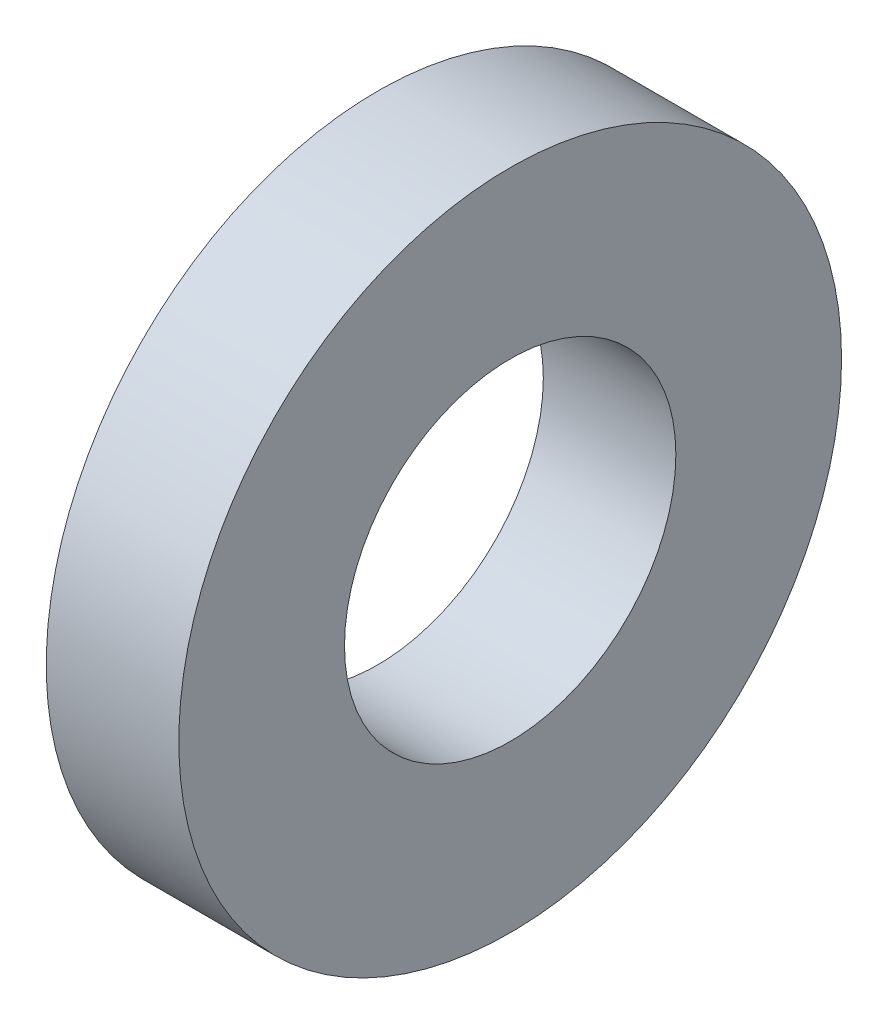
SolidWorks part; units mm, degrees
material "Nylon 101"
ref_plane "Front Plane" through (0, 0, 0) normal (0, 0, 1) x (1, 0, 0)
ref_plane "Top Plane" through (0, 0, 0) normal (0, 1, 0) x (1, 0, 0)
ref_plane "Right Plane" through (0, 0, 0) normal (1, 0, 0) x (0, 0, -1)
sketch "Sketch1" plane through (0, 0, 0) normal (1, 0, 0) x (0, 0, -1)
  circle A0 centre (0, 0) radius 2.5
  circle A1 centre (0, 0) radius 1.25
  dimension "D2" = 5
  dimension "D1" = 2.5
extrude "Boss-Extrude1" add sketch "Sketch1" along normal blind 1
